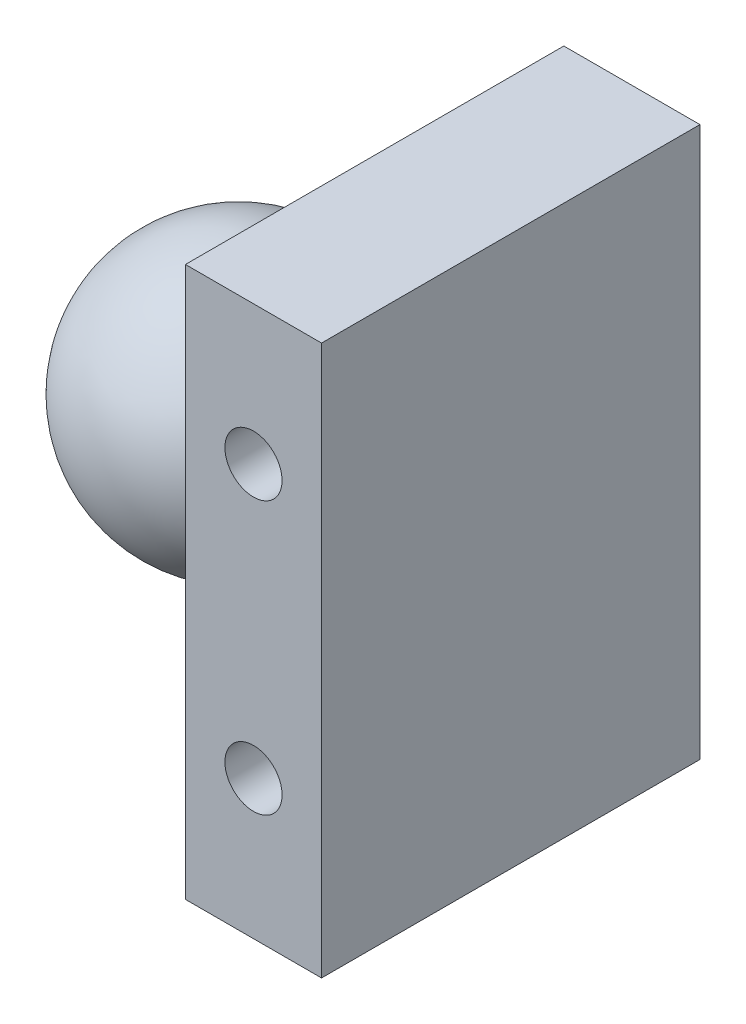
SolidWorks part; units mm, degrees
material "ABS"
ref_plane "Front" through (0, 0, 0) normal (0, 0, 1) x (1, 0, 0)
ref_plane "Top" through (0, 0, 0) normal (0, 1, 0) x (1, 0, 0)
ref_plane "Right" through (0, 0, 0) normal (1, 0, 0) x (0, 0, -1)
sketch "Esquisse1" plane through (0, 0, 0) normal (0, 0, 1) x (1, 0, 0)
  line L1 (-2.5, 10.1) -> (2.5, 10.1)
  line L2 (-2.5, 10.1) -> (-2.5, -10.1)
  line L3 (-2.5, -10.1) -> (2.5, -10.1)
  line L4 (2.5, 10.1) -> (2.5, -10.1)
  line L5 (-2.5, 10.1) -> (2.5, -10.1) construction
  line L6 (-2.5, -10.1) -> (2.5, 10.1) construction
  point P0 (0, 0)
  dimension "D1" = 5
  dimension "D2" = 20.2
extrude "Boss.-Extru.1" add sketch "Esquisse1" along normal blind 13.9
sketch "Esquisse4" plane through (0, 0, 0) normal (0, 0, -1) x (-1, 0, 0)
  line L0 (-2.5, 10.1) -> (2.5, 10.1) construction
  line L1 (-2.5, -10.1) -> (-2.5, 10.1) construction
  circle A0 centre (0, 5) radius 1.05
  circle A2 centre (0, -5) radius 1.05
  dimension "D1" = 2
  dimension "D2" = 5.1
  dimension "D3" = 2.1
  dimension "D4" = 2.5
extrude "Enlèv. mat.-Extru.1" cut sketch "Esquisse4" against normal through all
sketch "Sketch1" plane through (-2.5, 0, 0) normal (-1, 0, 0) x (0, 0, 1)
  circle A0 centre (6.95, 0) radius 3
  dimension "D1" = 6
  dimension "D2" = 10.1
  dimension "D3" = 6.95
extrude "Boss-Extrude1" add sketch "Sketch1" along normal blind 1
ref_plane "Plane1" through (0, 0, 0) normal (0, -1, 0) x (-1, 0, 0)
sketch "Sketch5" plane through (0, 0, 0) normal (0, -1, 0) x (-1, 0, 0)
  line L0 (3.5, -6.95) -> (12.5, -6.95)
  line L1 (3.5, -9.95) -> (3.5, -3.95) construction
  line L2 (3.5, -6.95) -> (3.5, -9.95)
  line L3 (7.5, -6.95) -> (3.5, -9.95) construction
  arc A0 (12.5, -6.95) -> (3.5, -9.95) centre (7.5, -6.95) cw
  dimension "D1" = 5
revolve "Revolve4" add sketch "Sketch5" angle 360 about L0
